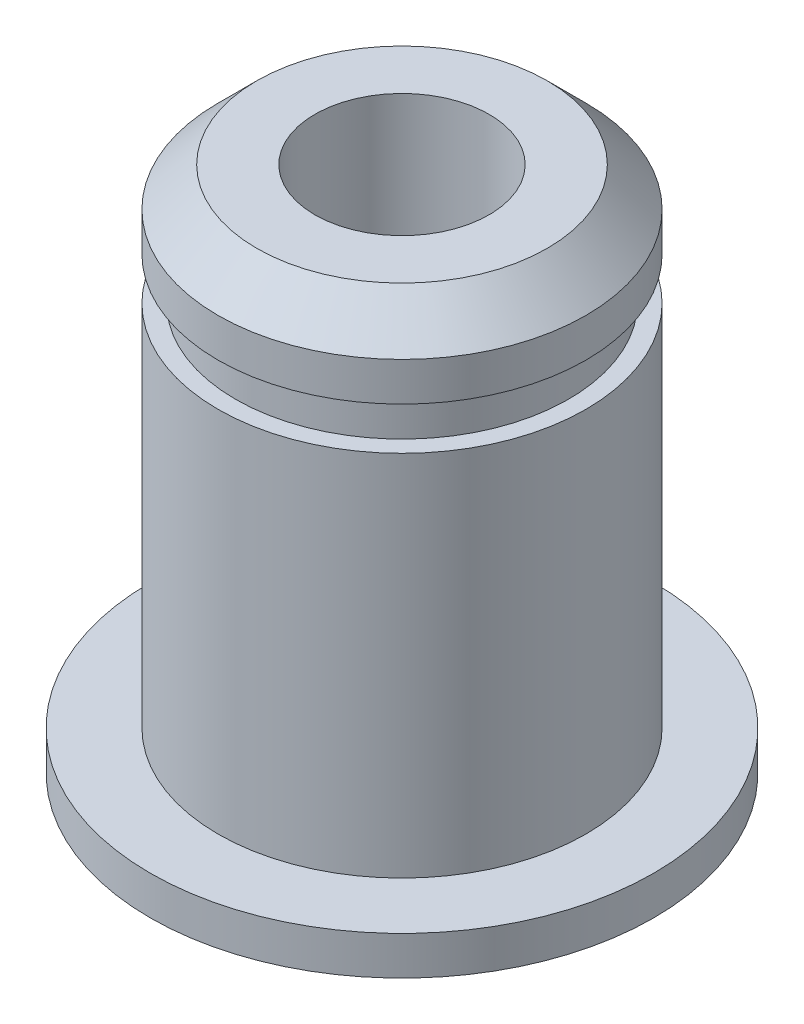
SolidWorks part; units mm, degrees
ref_plane "Front Plane" through (0, 0, 0) normal (0, 0, 1) x (1, 0, 0)
ref_plane "Top Plane" through (0, 0, 0) normal (0, 1, 0) x (1, 0, 0)
ref_plane "Right Plane" through (0, 0, 0) normal (1, 0, 0) x (0, 0, -1)
sketch "Sketch1" plane through (0, 0, 0) normal (0, 0, 1) x (1, 0, 0)
  line L0 (0, 0) -> (6.5, 0)
  line L1 (6.5, 0) -> (6.5, 1)
  line L2 (6.5, 1) -> (4.75, 1)
  line L3 (4.75, 1) -> (4.75, 10.5)
  line L4 (4.75, 10.5) -> (4.3, 10.5)
  line L5 (4.3, 10.5) -> (4.3, 11.6)
  line L6 (4.3, 11.6) -> (4.75, 11.6)
  line L7 (4.75, 11.6) -> (4.75, 13.6)
  line L8 (4.75, 13.6) -> (0, 13.6)
  line L9 (0, 13.6) -> (0, 0)
  line L10 (0, 22.9918) -> (0, -6.294) construction
  line L12 (0, 0) -> (2.25, 0)
  line L13 (0, 0) -> (0, 13.6)
  line L14 (0, 13.6) -> (2.25, 13.6)
  line L15 (2.25, 0) -> (2.25, 13.6)
  dimension "D1" = 6.5
  dimension "D2" = 4.3
  dimension "D3" = 1
  dimension "D4" = 9.5
  dimension "D5" = 2.5
  dimension "D6" = 1.1
  dimension "D7" = 2
  dimension "D8" = 6.5
  dimension "D9" = 4.75
  dimension "D10" = 4.3
revolve "Revolve1" add sketch "Sketch1" angle 360 about L9
chamfer "Chamfer1" distance 1 angle 45 1 edges at (0, 13.6, 4.75)
